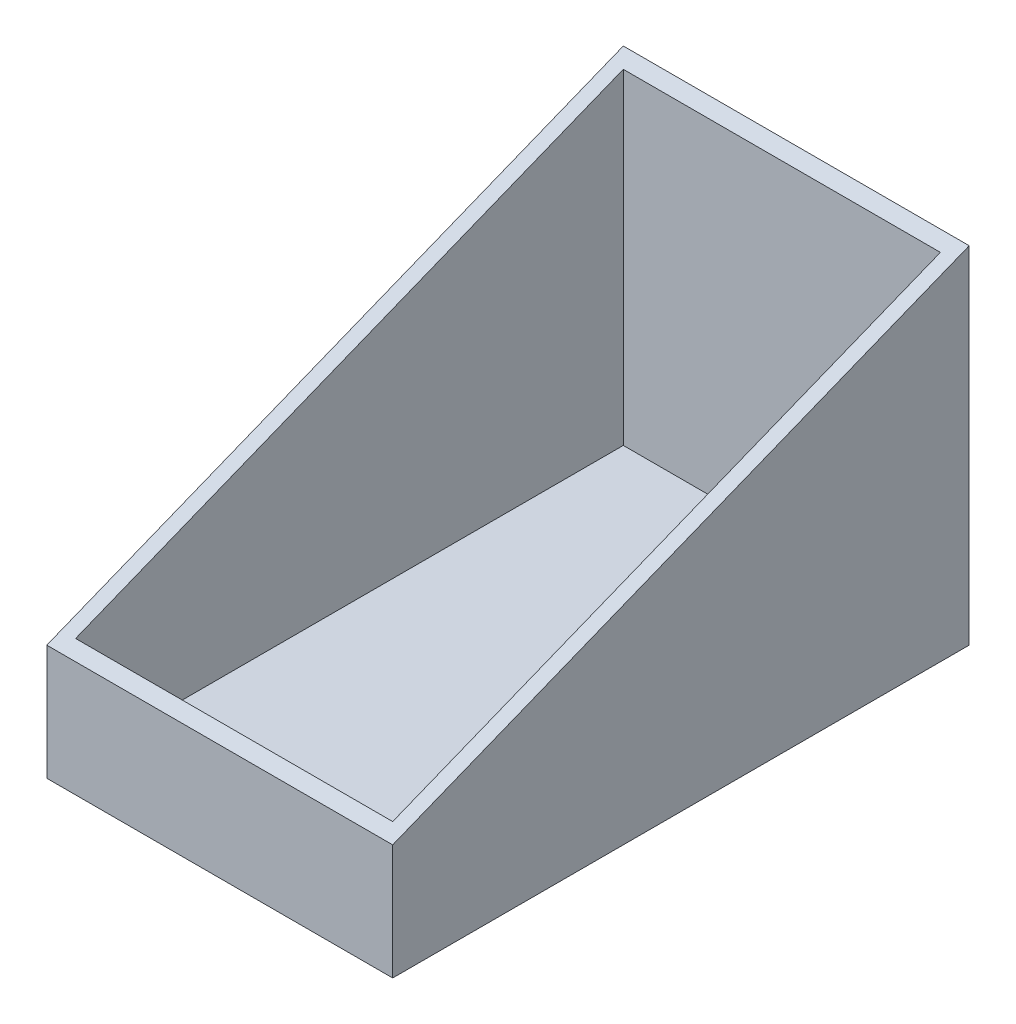
SolidWorks part; units mm, degrees
ref_plane "Front Plane" through (0, 0, 0) normal (0, 0, 1) x (1, 0, 0)
ref_plane "Top Plane" through (0, 0, 0) normal (0, 1, 0) x (1, 0, 0)
ref_plane "Right Plane" through (0, 0, 0) normal (1, 0, 0) x (0, 0, -1)
sketch "Sketch1" plane through (0, 0, 0) normal (1, 0, 0) x (0, 0, -1)
  line L0 (254, 152.4) -> (0, 50.8)
  line L1 (0, 0) -> (254, 0)
  line L2 (0, 0) -> (0, 152.4)
  line L3 (0, 152.4) -> (254, 152.4)
  line L4 (254, 0) -> (254, 152.4)
  dimension "D1" = 50.8
  dimension "D2" = 254
  dimension "D3" = 152.4
extrude "Boss-Extrude1" add sketch "Sketch1" along normal blind 152.4 contours L1 L4 L0 L2
shell "Shell1" thickness 6.35
